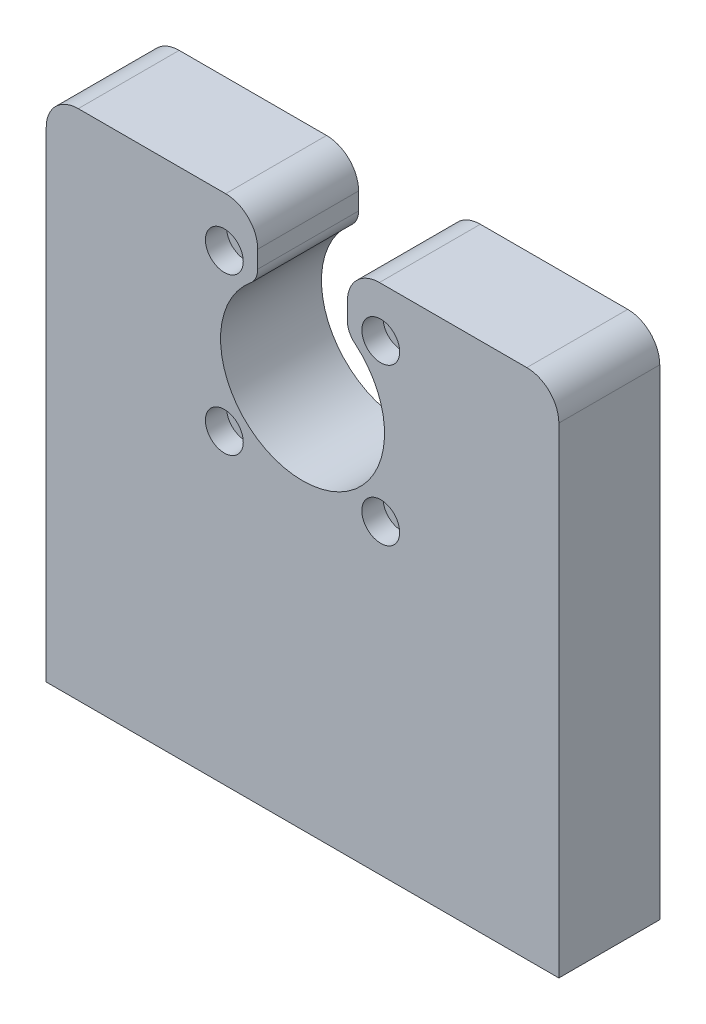
SolidWorks part; units mm, degrees
ref_plane "Front Plane" through (0, 0, 0) normal (0, 0, 1) x (1, 0, 0)
ref_plane "Top Plane" through (0, 0, 0) normal (0, 1, 0) x (1, 0, 0)
ref_plane "Right Plane" through (0, 0, 0) normal (1, 0, 0) x (0, 0, -1)
sketch "Sketch1" plane through (0, 0, 0) normal (0, 0, 1) x (1, 0, 0)
  line L0 (50.8, 25.4) -> (8.89, 25.4)
  line L2 (50.8, 25.4) -> (50.8, -76.2)
  line L3 (50.8, -76.2) -> (-50.8, -76.2)
  line L4 (-50.8, 25.4) -> (-50.8, -76.2)
  line L5 (16.9333, 25.4) -> (-50.8, -76.2) construction
  line L6 (50.8, -76.2) -> (-16.9333, 25.4) construction
  line L7 (-8.89, 25.4) -> (-50.8, 25.4)
  line L9 (-8.89, 25.4) -> (-8.89, 13.3029)
  line L10 (-8.89, 13.3029) -> (8.89, 13.3029)
  line L11 (8.89, 25.4) -> (8.89, 13.3029)
  line L12 (-50.8, -76.2) -> (-50.8, 19.05) construction
  circle A2 centre (0, 0) radius 16 construction
  point P0 (0, 0)
  point P2 (0, 25.4)
  dimension "D1" = 17.78
  dimension "D2" = 101.6
extrude "Boss-Extrude1" add sketch "Sketch1" along normal blind 20
sketch "Sketch2" plane through (0, 0, 20) normal (0, 0, 1) x (1, 0, 0)
  circle A0 centre (0, 0) radius 16.25
  circle A1 centre (-15.5, -15.5) radius 2.15
  circle A2 centre (-15.5, 15.5) radius 2.15
  circle A3 centre (15.5, -15.5) radius 2.15
  circle A4 centre (15.5, 15.5) radius 2.15
  dimension "D1" = 32.5
  dimension "D2" = 4.3
extrude "Cut-Extrude1" cut sketch "Sketch2" against normal up to surface (20 mm away) up to face at (0, -3.0243, 0)
sketch "Sketch5" plane through (0, 0, 20) normal (0, 0, 1) x (1, 0, 0)
  circle A0 centre (-15.5, 15.5) radius 3.75
  circle A1 centre (15.5, 15.5) radius 3.75
  circle A2 centre (15.5, -15.5) radius 3.75
  circle A3 centre (-15.5, -15.5) radius 3.75
  dimension "D1" = 7.5
extrude "Cut-Extrude4" cut sketch "Sketch5" against normal blind 4.2
fillet "Fillet3" radius 4 2 edges at (8.89, 13.6026, 10) (-8.89, 13.6026, 10)
fillet "Fillet4" radius 6.35 4 edges at (-50.8, 25.4, 10) (-8.89, 25.4, 10) (8.89, 25.4, 10) (50.8, 25.4, 10)
